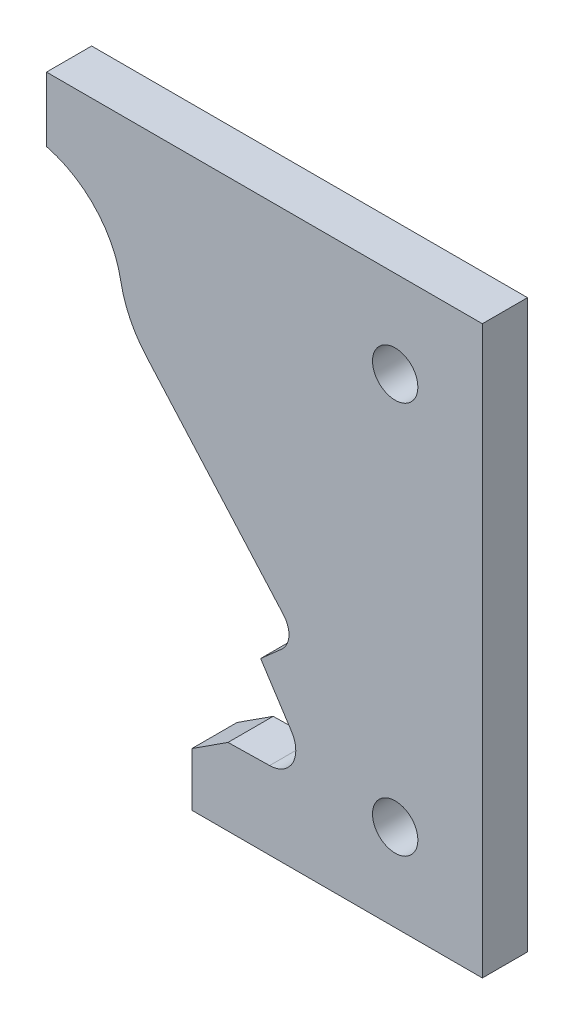
SolidWorks part; units mm, degrees
material "6061 Alloy"
ref_plane "X-Y Datum" through (0, 0, 0) normal (0, 0, 1) x (1, 0, 0)
ref_plane "X-Z Datum" through (0, 0, 0) normal (0, 1, 0) x (1, 0, 0)
ref_plane "Y-Z Datum" through (0, 0, 0) normal (1, 0, 0) x (0, 0, -1)
sketch "Sketch1" plane through (0, 0, 0) normal (0, 0, 1) x (1, 0, 0)
  line L10 (34.8147, -34.7512) -> (40.2452, -29.9528)
  line L11 (40.2452, -29.9528) -> (18.1591, -4.957)
  line L13 (24.7935, -51.1262) -> (24.7935, -58.9143)
  line L21 (24.7935, -51.1262) -> (30.06, -47.7178)
  line L22 (36.8599, -37.9114) -> (34.8147, -34.7512)
  line L25 (36.127, -47.6015) -> (30.06, -47.7178)
  line L30 (24.7935, -58.9143) -> (50.1935, -58.9143)
  line L35 (3.6159, 23.6357) -> (3.6159, 14.2365)
  line L36 (3.6159, 14.2365) -> (2.4931, -58.9143)
  line L37 (24.7935, -58.9143) -> (2.4931, -58.9143)
  line L38 (3.6159, 23.6357) -> (67.1159, 23.6357)
  line L39 (67.1159, 23.6357) -> (67.1159, -58.9143)
  line L40 (67.1159, -58.9143) -> (50.1935, -58.9143)
  line L42 (36.8599, -37.9114) -> (39.3256, -41.7214)
  arc A5 (14.4437, 2.6709) -> (3.6159, 14.2365) centre (0, 0) ccw
  arc A6 (18.1591, -4.957) -> (14.4437, 2.6709) centre (30.06, 5.5586) cw
  arc A18 (14.4651, 2.5577) -> (3.6159, 14.2374) centre (0.0072, 0.0067) ccw
  arc A20 (36.127, -47.6015) -> (39.3256, -41.7214) centre (36.127, -43.7915) ccw
  point P8 (36.127, -43.7915)
  dimension "D2" = 63.5
  dimension "D8" = 15.8811
  dimension "D3" = 3.81
  dimension "D10" = 25.4
extrude "Boss-Extrude2" add sketch "Sketch1" along normal mid plane 6.5786
fillet "Fillet4" radius 3.175 1 edges at (40.2452, -29.9528, 0)
sketch "Sketch2" plane through (0, 0, 3.2893) normal (0, 0, 1) x (1, 0, 0)
  line L0 (3.6159, 23.6357) -> (67.1159, 23.6357) construction
  line L1 (67.1159, 23.6357) -> (67.1159, -58.9143) construction
  line L2 (24.7935, -58.9143) -> (67.1159, -58.9143) construction
  point P0 (54.4159, 10.9357)
  point P1 (54.4159, -46.2143)
  dimension "D1" = 12.7
  dimension "D2" = 12.7
  dimension "D3" = 12.7
  dimension "D4" = 12.7
hole_wizard "#97 (0.26) Diameter Hole1" positions "3DSketch1" profile "Sketch3" hole size "#97" standard "ANSI Inch" end condition through all
sketch3d "3DSketch1"
  point P0 (54.4159, 10.9357, 3.2893)
  point P3 (54.4159, -46.2143, 3.2893)
sketch "Sketch3" plane through (54.4159, 10.9357, 3.2893) normal (1, 0, 0) x (0, -1, 0)
  line L0 (0, 0) -> (0, 6.5786)
  line L1 (0, 6.5786) -> (3.302, 6.5786)
  line L2 (3.302, 6.5786) -> (3.302, 0)
  line L5 (3.302, 0) -> (0, 0)
  line L11 (0, -6.35) -> (0, 107.95) construction
  dimension "Thru Hole Dia." = 6.604
  dimension "Thru Hole Depth" = 6.5786
